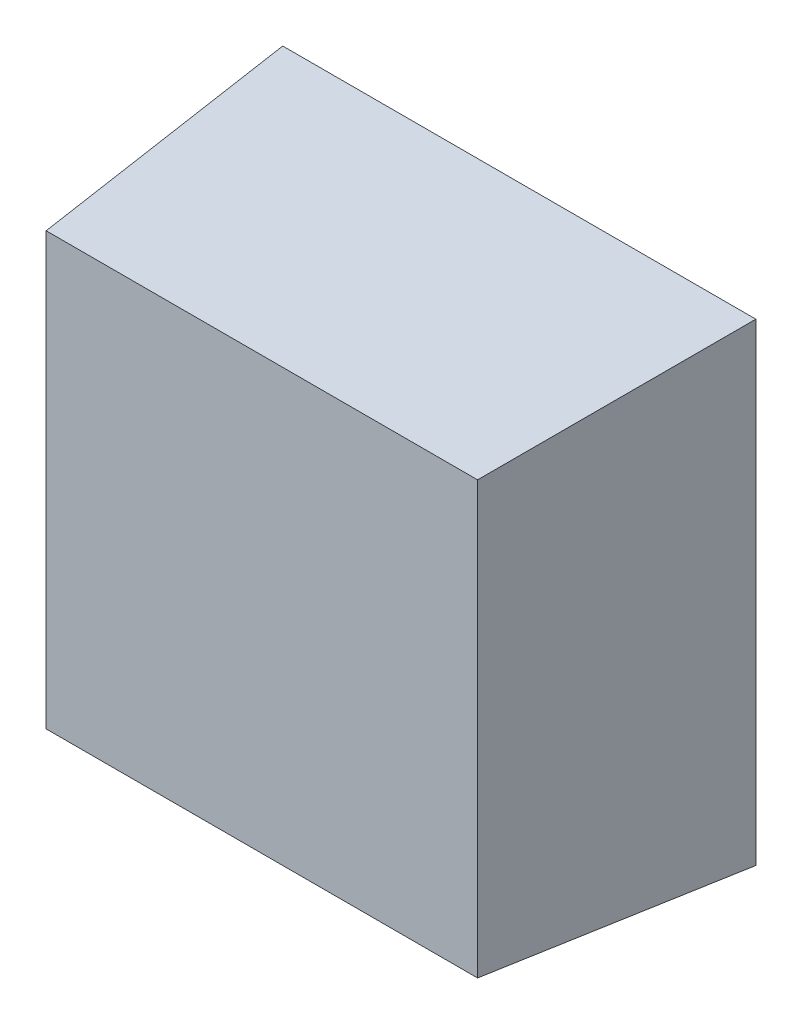
SolidWorks part; units mm, degrees
ref_plane "Front Plane" through (0, 0, 0) normal (0, 0, 1) x (1, 0, 0)
ref_plane "Top Plane" through (0, 0, 0) normal (0, 1, 0) x (1, 0, 0)
ref_plane "Right Plane" through (0, 0, 0) normal (1, 0, 0) x (0, 0, -1)
sketch "Sketch1" plane through (0, 0, 0) normal (0, 0, 1) x (1, 0, 0)
  line L1 (0, 0) -> (40, 0)
  line L2 (0, 0) -> (0, 40)
  line L3 (0, 40) -> (40, 40)
  line L4 (40, 0) -> (40, 40)
extrude "Boss-Extrude1" add sketch "Sketch1" along normal blind 20
draft "Draft1" type of draft neutral plane draft angle 10 faces to draft 2 face at (20, 40, 10) face at (40, 20, 10) neutral plane through (0, 0, 0) neutral plane normal (0, 0, -1) reverse direction yes parameters "D1"=10
